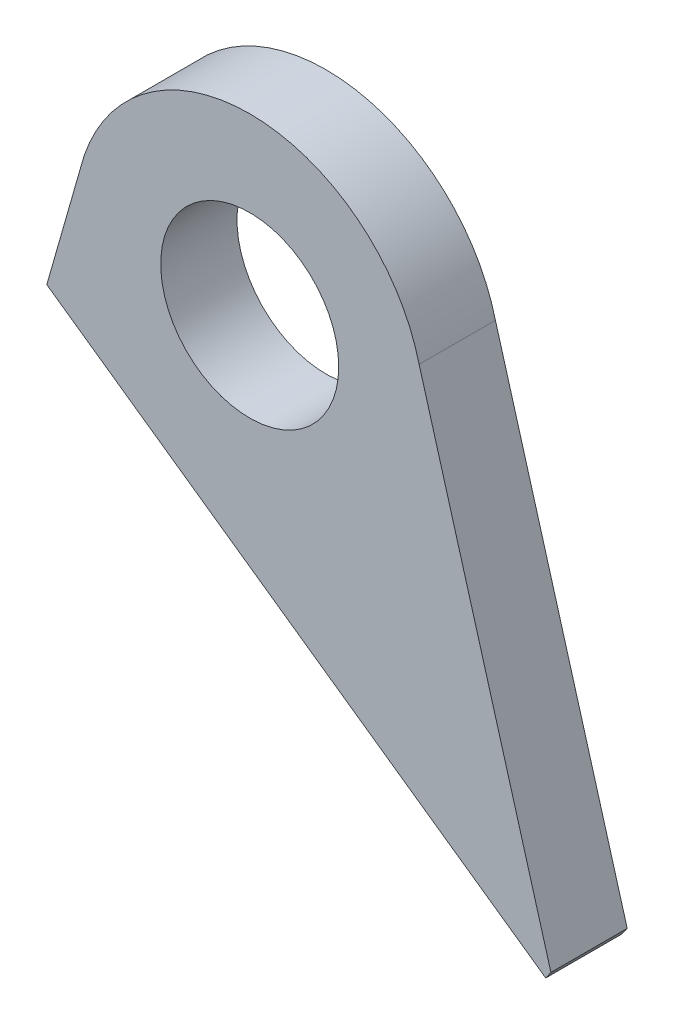
SolidWorks part; units mm, degrees
material "AISI 304"
ref_plane "Front" through (0, 0, 0) normal (0, 0, 1) x (1, 0, 0)
ref_plane "Top" through (0, 0, 0) normal (0, 1, 0) x (1, 0, 0)
ref_plane "Right" through (0, 0, 0) normal (1, 0, 0) x (0, 0, -1)
sketch "Sketch1" plane through (0, 0, 0) normal (0, 0, 1) x (1, 0, 0)
  line L0 (-60, -60) -> (-33.3082, 33.3082)
  line L1 (-60, -60) -> (60, -60)
  line L5 (-60, -60) -> (33.3082, 33.3082) construction
  line L6 (-33.3082, 33.3082) -> (60, -60) construction
  line L7 (60, -60) -> (33.3082, 33.3082)
  arc A0 (-33.3082, 33.3082) -> (33.3082, 33.3082) centre (0, 25) cw
  point P0 (0, 0)
  dimension "D1" = 120
  dimension "D2" = 85
extrude "Boss-Extrude1" add sketch "Sketch1" along normal blind 15 contours L0 A0 L7 L1
sketch "Sketch2" plane through (0, 0, 15) normal (0, 0, 1) x (1, 0, 0)
  circle A0 centre (0, 25) radius 17.5
  dimension "D1" = 35
extrude "Cut-Extrude1" cut sketch "Sketch2" against normal through all
sketch "Sketch3" plane through (0, 0, 15) normal (0, 0, 1) x (1, 0, 0)
  line L0 (60, -60) -> (-39.8974, 10.2737)
  line L1 (-60, -60) -> (-33.3082, 33.3082) construction
  line L2 (-39.8974, 10.2737) -> (-60, -60)
  line L3 (-60, -60) -> (60, -60) construction
  line L4 (-60, -60) -> (60, -60)
  circle A0 centre (0, 25) radius 17.5 construction
  dimension "D1" = 35
extrude "Cut-Extrude2" cut sketch "Sketch3" against normal blind 15
sketch "Sketch4" plane through (-8.3729, -11.9025, 0) normal (-0.5754, -0.8179, 0) x (0.8179, -0.5754, 0)
  line L0 (83.5956, 0) -> (-38.5432, 0) construction
  line L1 (83.5956, 15) -> (81.3956, 15)
  line L2 (83.5956, 15) -> (83.5956, 0)
  line L3 (83.5956, 0) -> (81.3956, 0)
  line L4 (81.3956, 15) -> (81.3956, 0)
  dimension "D1" = 2.2
extrude "Cut-Extrude3" cut sketch "Sketch4" against normal blind 10
